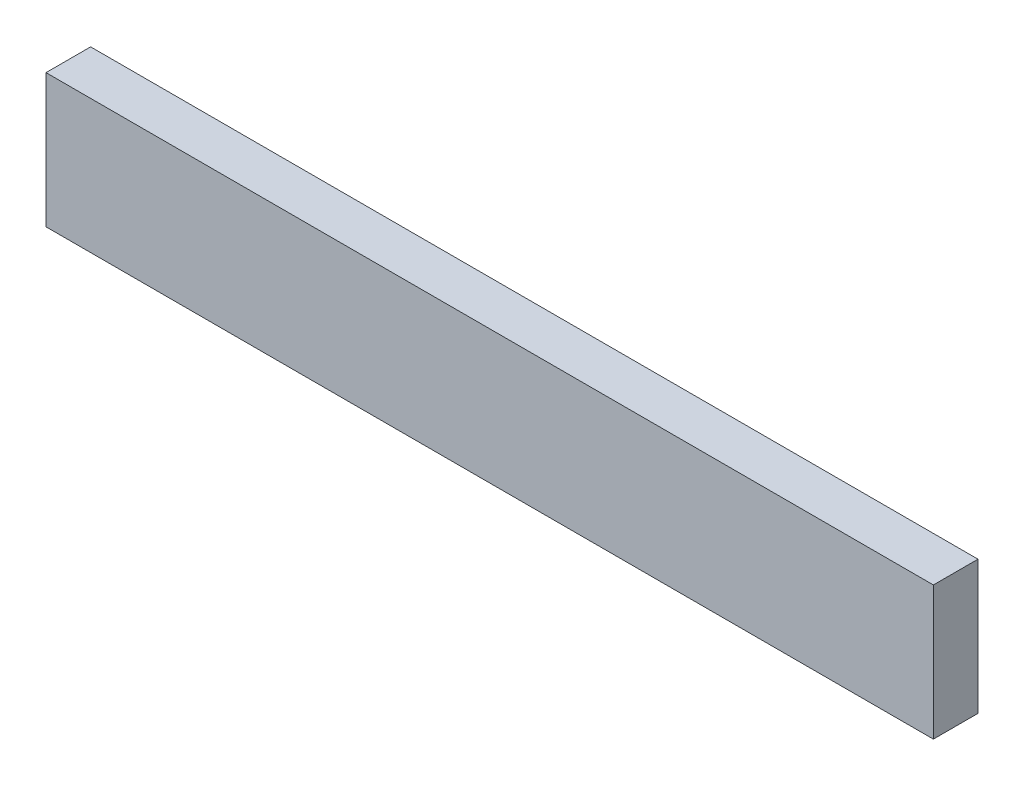
SolidWorks part; units mm, degrees
ref_plane "Front Plane" through (0, 0, 0) normal (0, 0, 1) x (1, 0, 0)
ref_plane "Top Plane" through (0, 0, 0) normal (0, 1, 0) x (1, 0, 0)
ref_plane "Right Plane" through (0, 0, 0) normal (1, 0, 0) x (0, 0, -1)
sketch "Sketch1" plane through (0, 0, 0) normal (0, 0, 1) x (1, 0, 0)
  line L1 (-139.2, 20.95) -> (139.2, 20.95)
  line L2 (-139.2, 20.95) -> (-139.2, -20.95)
  line L3 (-139.2, -20.95) -> (139.2, -20.95)
  line L4 (139.2, 20.95) -> (139.2, -20.95)
  line L5 (-139.2, 20.95) -> (139.2, -20.95) construction
  line L6 (-139.2, -20.95) -> (139.2, 20.95) construction
  point P0 (0, 0)
  dimension "D1" = 41.9
  dimension "D2" = 278.4
extrude "Boss-Extrude1" add sketch "Sketch1" along normal blind 14
